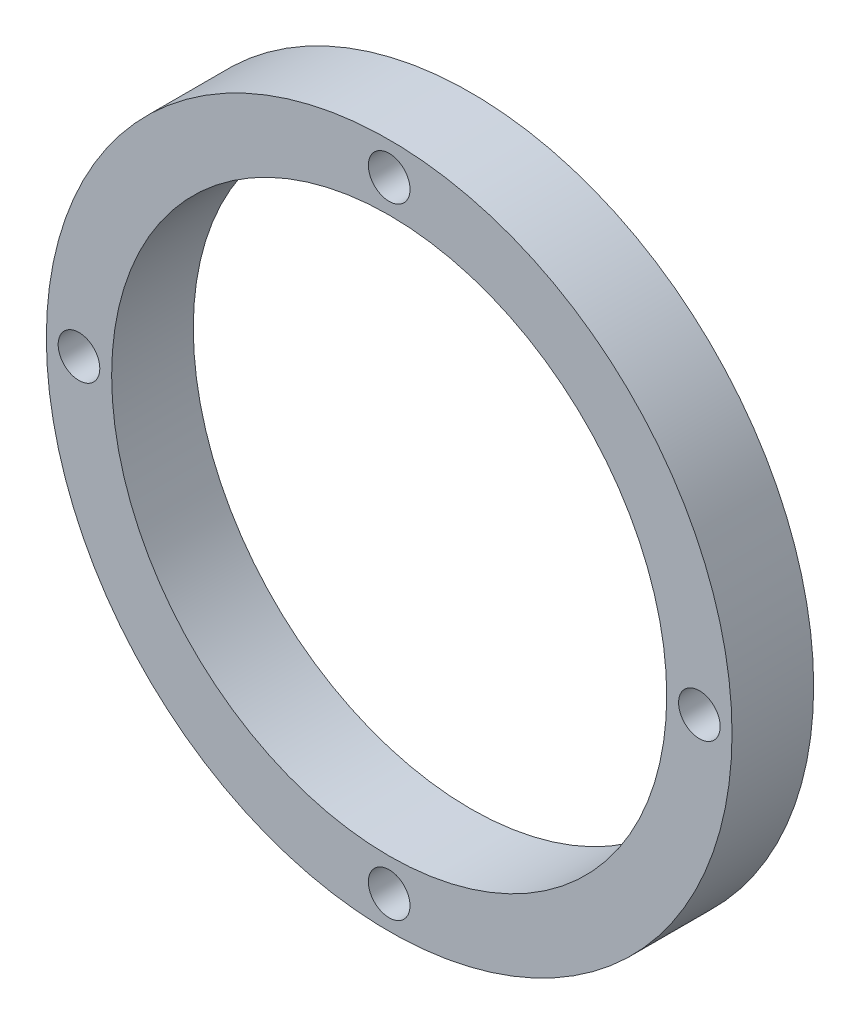
SolidWorks part; units mm, degrees
ref_plane "Front Plane" through (0, 0, 0) normal (0, 0, 1) x (1, 0, 0)
ref_plane "Top Plane" through (0, 0, 0) normal (0, 1, 0) x (1, 0, 0)
ref_plane "Right Plane" through (0, 0, 0) normal (1, 0, 0) x (0, 0, -1)
sketch "Sketch1" plane through (0, 0, 0) normal (0, 0, 1) x (1, 0, 0)
  line L0 (0, 50.718) -> (0, -48.9253) construction
  circle A0 centre (0, 0) radius 42
  circle A1 centre (0, 0) radius 34
  circle A2 centre (0, 38) radius 1.75
  circle A3 centre (38, 0) radius 1.75
  circle A4 centre (0, -38) radius 1.75
  circle A5 centre (-38, 0) radius 1.75
  point P17 (0, 0)
  dimension "D1" = 84
  dimension "D2" = 68
  dimension "D3" = 3.5
  dimension "D4" = 38
extrude "Boss-Extrude1" add sketch "Sketch1" along normal blind 10
sketch "Sketch2" plane through (0, 0, 10) normal (0, 0, 1) x (1, 0, 0)
  circle A0 centre (0, 38) radius 2.55
  circle A1 centre (38, 0) radius 2.55
  circle A2 centre (0, -38) radius 2.55
  circle A3 centre (-38, 0) radius 2.55
  point P12 (0, 0)
  dimension "D1" = 5.1
extrude "Cut-Extrude1" cut sketch "Sketch2" against normal blind 7
